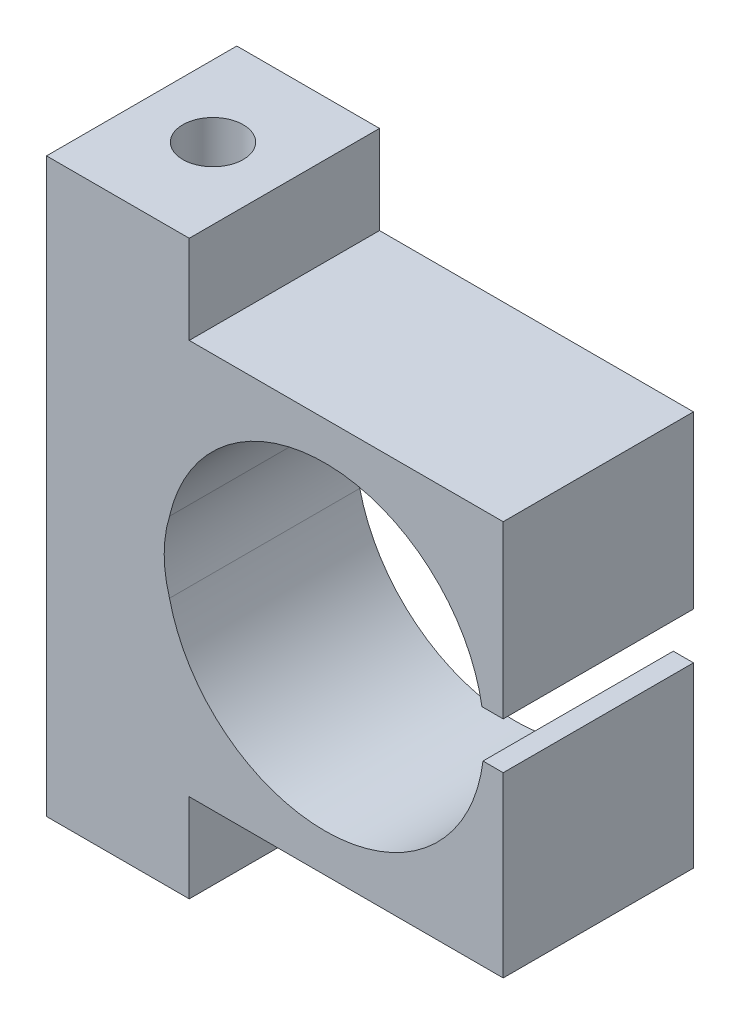
SolidWorks part; units mm, degrees
material "PE Alta densidad"
ref_plane "Alzado" through (0, 0, 0) normal (0, 0, 1) x (1, 0, 0)
ref_plane "Planta" through (0, 0, 0) normal (0, 1, 0) x (1, 0, 0)
ref_plane "Vista lateral" through (0, 0, 0) normal (1, 0, 0) x (0, 0, -1)
ref_plane "Plano1" through (0, 0, 0) normal (0, 0, -1) x (-1, 0, 0)
sketch "Croquis1" plane through (0, 0, 0) normal (0, 0, -1) x (-1, 0, 0)
  line L0 (-14.9321, 25.0679) -> (-14.9321, -25.0679)
  line L1 (-14.9321, -25.0679) -> (25.0679, -25.0679)
  line L2 (25.0679, -25.0679) -> (25.0679, 25.0679)
  line L3 (25.0679, 25.0679) -> (-14.9321, 25.0679)
extrude "Saliente-Extruir1" add sketch "Croquis1" against normal blind 20
sketch "Croquis2" plane through (0, 0, 20) normal (0, 0, 1) x (1, 0, 0)
  line L0 (14.9321, -25.0679) -> (14.9321, -15.7679)
  line L1 (14.9321, -15.7679) -> (-10.0679, -15.7679)
  line L2 (-10.0679, -15.7679) -> (-10.0679, -25.0679)
  line L3 (-10.0679, -25.0679) -> (14.9321, -25.0679)
extrude "Cortar-Extruir1" cut sketch "Croquis2" against normal through all
sketch "Croquis3" plane through (0, 0, 20) normal (0, 0, 1) x (1, 0, 0)
  line L0 (14.9321, 25.0679) -> (-10.0679, 25.0679)
  line L1 (-10.0679, 25.0679) -> (-10.0679, 15.7679)
  line L2 (-10.0679, 15.7679) -> (14.9321, 15.7679)
  line L3 (14.9321, 15.7679) -> (14.9321, 25.0679)
extrude "Cortar-Extruir2" cut sketch "Croquis3" against normal through all
sketch "Croquis4" plane through (0, 0, 20) normal (0, 0, 1) x (1, 0, 0)
  line L0 (14.9321, 2.8147) -> (12.3842, 2.8147)
  line L1 (12.5287, -2.0789) -> (14.9321, -2.0789)
  line L2 (14.9321, -2.0789) -> (14.9321, 2.8147)
  arc A0 (12.3842, 2.8147) -> (12.5287, -2.0789) centre (0, 0) cw
extrude "Cortar-Extruir3" cut sketch "Croquis4" against normal through all
ref_plane "Plano2" through (0, 0, 0) normal (0, -1, 0) x (1, 0, 0)
sketch "Croquis5" plane through (0, 0, 0) normal (0, -1, 0) x (1, 0, 0)
  line L0 (12.7, 20) -> (0, 20)
  line L1 (0, 20) -> (0, 0)
  line L2 (0, 0) -> (12.7, 0)
  line L3 (12.7, 0) -> (12.7, 20)
  line L4 (0, 20) -> (0, 0) construction
revolve "Cortar-Revolución1" cut sketch "Croquis5" angle 360 about L4
hole_wizard "Taladro1" positions "Croquis7" profile "Croquis6" legacy
sketch "Croquis7" plane through (0, -25.0679, 0) normal (0, -1, 0) x (-1, 0, 0)
  point P0 (17.5679, -9.9993)
sketch "Croquis6" plane through (-17.5679, -25.0679, 9.9993) normal (1, 0, 0) x (0, 0, -1)
  line L0 (0, 0) -> (0, 15)
  line L1 (0, 15) -> (3.175, 15)
  line L2 (3.175, 15) -> (3.175, 0)
  line L3 (3.175, 0) -> (0, 0)
  line L4 (0, 110) -> (0, -10) construction
  dimension "Diámetro" = 6.35
  dimension "Profundidad" = 15
hole_wizard "Taladro2" positions "Croquis9" profile "Croquis8" legacy
sketch "Croquis9" plane through (0, 25.0679, 0) normal (0, 1, 0) x (1, 0, 0)
  point P0 (-17.5679, -10)
sketch "Croquis8" plane through (-17.5679, 25.0679, 10) normal (1, 0, 0) x (0, 0, 1)
  line L0 (0, 0) -> (0, 15)
  line L1 (0, 15) -> (3.175, 15)
  line L2 (3.175, 15) -> (3.175, 0)
  line L3 (3.175, 0) -> (0, 0)
  line L4 (0, 110) -> (0, -10) construction
  dimension "Diámetro" = 6.35
  dimension "Profundidad" = 15
sketch "Croquis11" plane through (14.9321, 0, 0) normal (1, 0, 0) x (0, 0, -1)
  line L1 (-20, 15.7679) -> (0, 15.7679)
  line L2 (-20, 15.7679) -> (-20, 2.8147)
  line L3 (-20, 2.8147) -> (0, 2.8147)
  line L4 (0, 15.7679) -> (0, 2.8147)
  line L5 (-20, -2.0789) -> (0, -2.0789)
  line L6 (-20, -2.0789) -> (-20, -15.7679)
  line L7 (-20, -15.7679) -> (0, -15.7679)
  line L8 (0, -2.0789) -> (0, -15.7679)
extrude "Saliente-Extruir2" add sketch "Croquis11" along normal blind 5
sketch "Croquis12" plane through (0, 25.0679, 0) normal (0, 1, 0) x (1, 0, 0)
  line L0 (-25.0679, -20) -> (-10.0679, -20) construction
  line L1 (-25.0679, 0) -> (-10.0679, 0)
  line L2 (-25.0679, 0) -> (-25.0679, -20)
  line L3 (-25.0679, -20) -> (-10.0679, -20)
  line L4 (-10.0679, 0) -> (-10.0679, -20)
extrude "Saliente-Extruir3" add sketch "Croquis12" along normal blind 5
sketch "Croquis13" plane through (0, -25.0679, 0) normal (0, -1, 0) x (1, 0, 0)
  circle A0 centre (-17.5679, 9.9993) radius 3.175
extrude "Cortar-Extruir4" cut sketch "Croquis13" against normal blind 76
sketch "Croquis14" plane through (0, -25.0679, 0) normal (0, -1, 0) x (1, 0, 0)
  line L1 (-25.0679, 20) -> (-10.0679, 20)
  line L2 (-25.0679, 20) -> (-25.0679, 0)
  line L3 (-25.0679, 0) -> (-10.0679, 0)
  line L4 (-10.0679, 20) -> (-10.0679, 0)
extrude "Saliente-Extruir4" add sketch "Croquis14" along normal blind 5
sketch "Croquis15" plane through (0, 30.0679, 0) normal (0, 1, 0) x (1, 0, 0)
  circle A0 centre (-17.5679, -9.9993) radius 3.175
extrude "Cortar-Extruir5" cut sketch "Croquis15" against normal blind 72
sketch "Croquis16" plane through (0, 15.7679, 0) normal (0, 1, 0) x (1, 0, 0)
  line L1 (-10.0679, 0) -> (19.9321, 0)
  line L2 (-10.0679, 0) -> (-10.0679, -20)
  line L3 (-10.0679, -20) -> (19.9321, -20)
  line L4 (19.9321, 0) -> (19.9321, -20)
extrude "Saliente-Extruir5" add sketch "Croquis16" along normal blind 5 contours L2 L1 L4 L3
sketch "Croquis17" plane through (0, -15.7679, 0) normal (0, -1, 0) x (1, 0, 0)
  line L1 (-10.0679, 20) -> (19.9321, 20)
  line L2 (-10.0679, 20) -> (-10.0679, 0)
  line L3 (-10.0679, 0) -> (19.9321, 0)
  line L4 (19.9321, 20) -> (19.9321, 0)
extrude "Saliente-Extruir6" add sketch "Croquis17" along normal blind 5
sketch "Croquis20" plane through (19.9321, 0, 0) normal (1, 0, 0) x (0, 0, -1)
  line L0 (0, -20.7679) -> (0, -2.0789) construction
  line L1 (-20, 20.7679) -> (0, 20.7679)
  line L2 (-20, 20.7679) -> (-20, 2.8147)
  line L3 (-20, 2.8147) -> (0, 2.8147)
  line L4 (0, 20.7679) -> (0, 2.8147)
  line L5 (-20, -2.0789) -> (0, -2.0789)
  line L6 (-20, -2.0789) -> (-20, -20.7679)
  line L7 (-20, -20.7679) -> (0, -20.7679)
  line L8 (0, -2.0789) -> (0, -20.7679)
extrude "Saliente-Extruir7" add sketch "Croquis20" along normal blind 3
sketch "Croquis21" plane through (0, 0, 20) normal (0, 0, 1) x (1, 0, 0)
  circle A0 centre (4.1897, 0) radius 16.75
  dimension "D1" = 33.5
extrude "Cortar-Extruir8" cut sketch "Croquis21" against normal blind 43 contours A0
